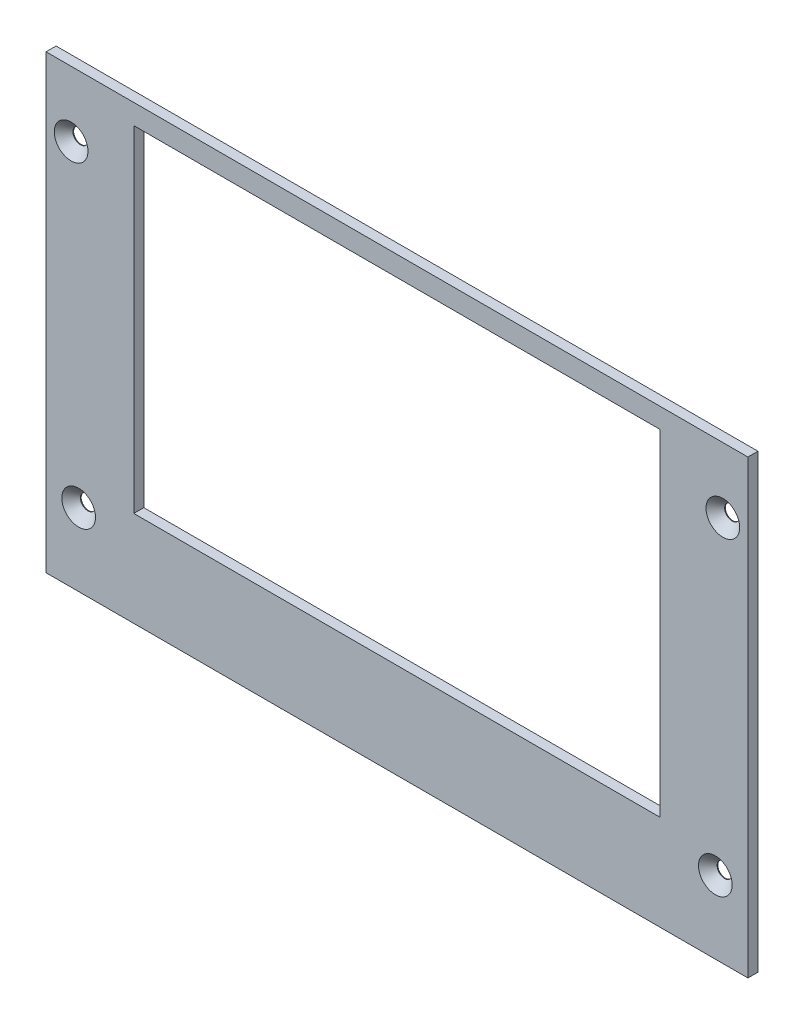
SolidWorks part; units mm, degrees
ref_plane "Front Plane" through (0, 0, 0) normal (0, 0, 1) x (1, 0, 0)
ref_plane "Top Plane" through (0, 0, 0) normal (0, 1, 0) x (1, 0, 0)
ref_plane "Right Plane" through (0, 0, 0) normal (1, 0, 0) x (0, 0, -1)
sketch "Sketch1" plane through (0, 0, 0) normal (0, 0, 1) x (1, 0, 0)
  line L4 (-68.527, -52.326) -> (71.473, -52.326)
  line L5 (71.473, -52.326) -> (71.473, 37.674)
  line L6 (71.473, 37.674) -> (-68.527, 37.674)
  line L7 (-68.527, 37.674) -> (-68.527, -52.326)
  line L8 (-68.527, -52.326) -> (71.473, -52.326)
  line L9 (71.473, -52.326) -> (71.473, 37.674)
  line L10 (71.473, 37.674) -> (-68.527, 37.674)
  line L11 (-68.527, 37.674) -> (-68.527, -52.326)
  line L12 (-51.027, 33.674) -> (-51.027, -33.326)
  line L13 (-51.027, -33.326) -> (53.973, -33.326)
  line L14 (53.973, -33.326) -> (53.973, 33.674)
  line L15 (53.973, 33.674) -> (-51.027, 33.674)
  line L16 (-51.027, 33.674) -> (-51.027, -33.326)
  line L17 (-51.027, -33.326) -> (53.973, -33.326)
  line L18 (53.973, -33.326) -> (53.973, 33.674)
  line L19 (53.973, 33.674) -> (-51.027, 33.674)
  dimension "D1" = 0
  dimension "D2" = 0
extrude "Boss-Extrude1" add sketch "Sketch1" along normal blind 2 contours L10 L11 L8 L9 L19 L18 L17 L16
sketch "Sketch2" plane through (0, 0, 0) normal (0, 0, -1) x (-1, 0, 0)
  circle A0 centre (62.027, -37.826) radius 1.5
  circle A1 centre (63.527, 24.674) radius 1.5
  circle A2 centre (-64.973, -37.826) radius 1.5
  circle A3 centre (-66.473, 24.674) radius 1.5
  dimension "D3" = 3
  dimension "D4" = 3
extrude "Cut-Extrude1" cut sketch "Sketch2" against normal through all
chamfer "Chamfer1" distance 1.86 4 edges at (-65.027, 24.674, 2) (-63.527, -37.826, 2) (64.973, 24.674, 2) (63.473, -37.826, 2)
sketch "Sketch3" plane through (0, 0, 2) normal (0, 0, 1) x (1, 0, 0)
  line L0 (61.473, -50.326) -> (61.473, 35.674) construction
  line L1 (61.473, 35.674) -> (5.433, 35.674) construction
  line L2 (61.473, -50.326) -> (0, -50.326) construction
  line L4 (71.473, 37.674) -> (-68.527, 37.674)
  line L5 (-68.527, 37.674) -> (-68.527, -52.326)
  line L6 (-68.527, -52.326) -> (71.473, -52.326)
  line L7 (71.473, -52.326) -> (71.473, 37.674)
  line L8 (71.473, 37.674) -> (-68.527, 37.674) construction
  line L9 (-68.527, 37.674) -> (-68.527, -52.326) construction
  line L10 (-68.527, -52.326) -> (71.473, -52.326) construction
  line L11 (71.473, -52.326) -> (71.473, 37.674) construction
  line L12 (54.473, -28.326) -> (39.448, -28.18) construction
  line L13 (-53.527, -28.18) -> (56.473, -28.18) construction
  line L14 (56.473, 30.674) -> (32.8373, 30.674) construction
  line L15 (56.473, 30.674) -> (-53.527, 30.674) construction
  line L16 (0, -50.326) -> (-58.527, -50.326) construction
  line L17 (-58.527, -50.326) -> (-58.527, -18.1481) construction
  dimension "D2" = 10
  dimension "D1" = 0
sketch "Sketch8" plane through (0, 0, 0) normal (0, 0, -1) x (-1, 0, 0)
  line L0 (-71.473, -52.326) -> (-71.473, 37.674) construction
  line L1 (-61.373, -50.226) -> (58.427, -50.226)
  line L2 (-61.373, -50.226) -> (-61.373, 35.574)
  line L3 (-61.373, 35.574) -> (58.427, 35.574)
  line L4 (58.427, -50.226) -> (58.427, 35.574)
  line L5 (57.427, 34.574) -> (-60.373, 34.574)
  line L6 (57.427, 34.574) -> (57.427, -49.226)
  line L7 (57.427, -49.226) -> (-60.373, -49.226)
  line L8 (-60.373, 34.574) -> (-60.373, -49.226)
  line L9 (68.527, -52.326) -> (-71.473, -52.326) construction
  line L10 (-71.473, 37.674) -> (68.527, 37.674) construction
  line L11 (68.527, 37.674) -> (68.527, -52.326) construction
  line L13 (-60.373, -49.226) -> (-60.373, -50.226)
  line L14 (-60.373, 34.574) -> (-60.373, 35.574)
  line L15 (57.427, 34.574) -> (57.427, 35.574)
  line L16 (57.427, -49.226) -> (57.427, -50.226)
  dimension "D1" = 10.1
  dimension "D2" = 2.1
  dimension "D3" = 1
  dimension "D4" = 1
  dimension "D5" = 2.1
  dimension "D6" = 1
  dimension "D7" = 1
  dimension "D8" = 10.1
extrude "Boss-Extrude3" add sketch "Sketch8" along normal blind 1 contours L16 L7 L13 L1 | L5 L15 L3 L14
